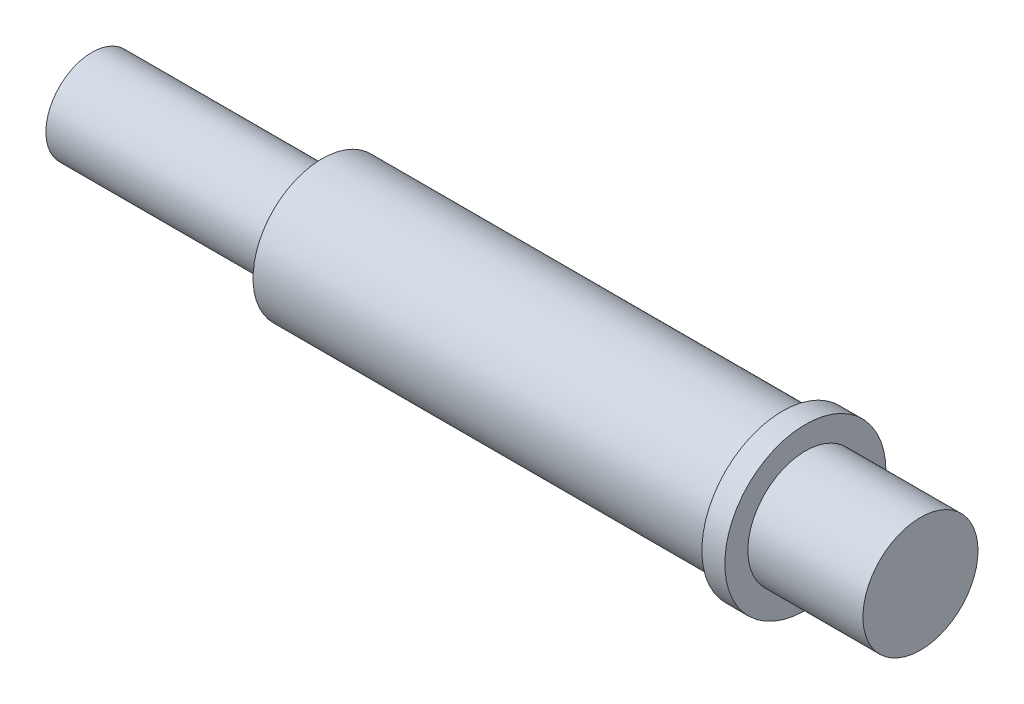
SolidWorks part; units mm, degrees
ref_plane "Front" through (0, 0, 0) normal (0, 0, 1) x (1, 0, 0)
ref_plane "Top" through (0, 0, 0) normal (0, 1, 0) x (1, 0, 0)
ref_plane "Right" through (0, 0, 0) normal (1, 0, 0) x (0, 0, -1)
sketch "Эскиз3" plane through (0, 0, 0) normal (1, 0, 0) x (0, 0, -1)
  circle A0 centre (0, 0) radius 20
extrude "part-1" add sketch "Эскиз3" along normal blind 100
sketch "Эскиз4" plane through (100, 0, 0) normal (1, 0, 0) x (0, 0, -1)
  circle A0 centre (0, 0) radius 30
extrude "part-2" add sketch "Эскиз4" along normal blind 200
sketch "Эскиз5" plane through (300, 0, 0) normal (1, 0, 0) x (0, 0, -1)
  circle A0 centre (0, 0) radius 35
extrude "part-3" add sketch "Эскиз5" along normal blind 10
sketch "Эскиз6" plane through (310, 0, 0) normal (1, 0, 0) x (0, 0, -1)
  circle A0 centre (0, 0) radius 25
extrude "part-4" add sketch "Эскиз6" along normal blind 50
